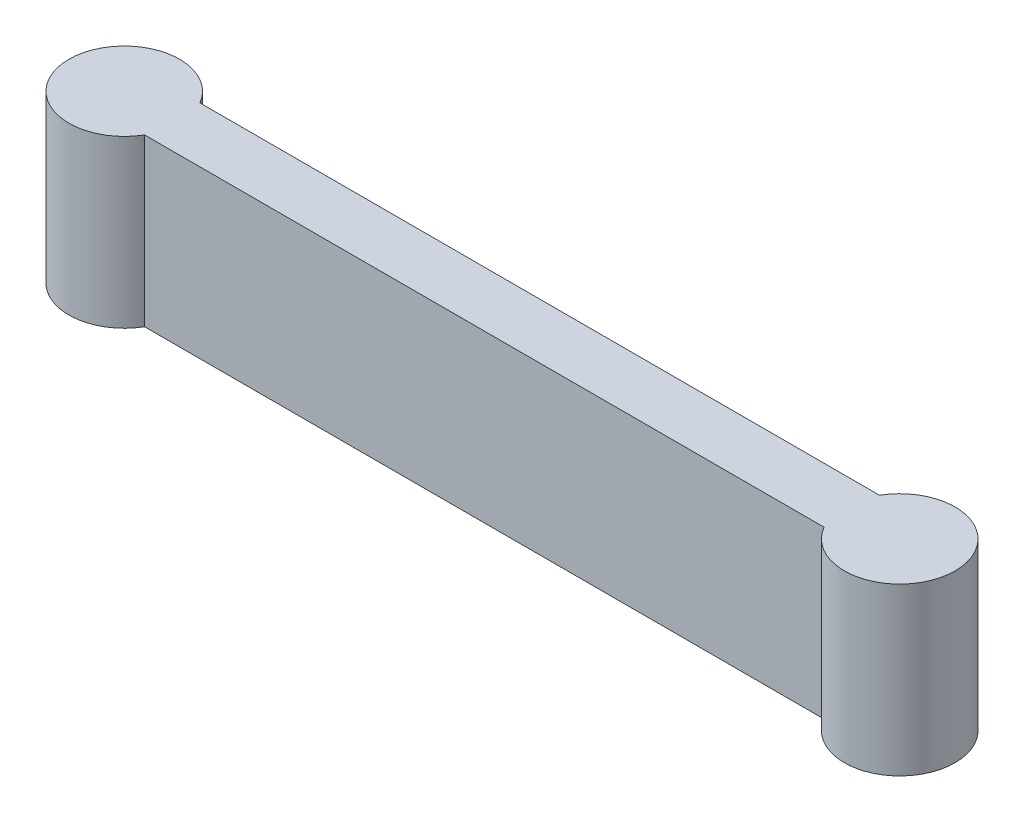
SolidWorks part; units mm, degrees
ref_plane "Front Plane" through (0, 0, 0) normal (0, 0, 1) x (1, 0, 0)
ref_plane "Top Plane" through (0, 0, 0) normal (0, 1, 0) x (1, 0, 0)
ref_plane "Right Plane" through (0, 0, 0) normal (1, 0, 0) x (0, 0, -1)
sketch "Sketch1" plane through (0, 0, 0) normal (0, 1, 0) x (1, 0, 0)
  line L0 (43.3013, -25) -> (656.6987, -25)
  line L1 (43.3013, -25) -> (43.3013, 25) construction
  line L2 (656.6987, 25) -> (43.3013, 25)
  arc A0 (43.3013, -25) -> (43.3013, 25) centre (0, 0) cw
  arc A1 (-49.8279, 4.1449) -> (49.8279, -4.1449) centre (0, 0) ccw construction
  arc A2 (656.6987, -25) -> (656.6987, 25) centre (700, 0) ccw
  dimension "D1" = 50
  dimension "D2" = 700
extrude "Boss-Extrude1" add sketch "Sketch1" along normal up to surface (75 mm away) and the other way up to surface (75 mm away)
ref_point "Point1"
sketch3d "3DSketch1"
  line L0 (700, 0, 0) -> (700, 356.4494, 0)
  line L1 (700, 0, 0) -> (995.7572, 0, 0) construction
